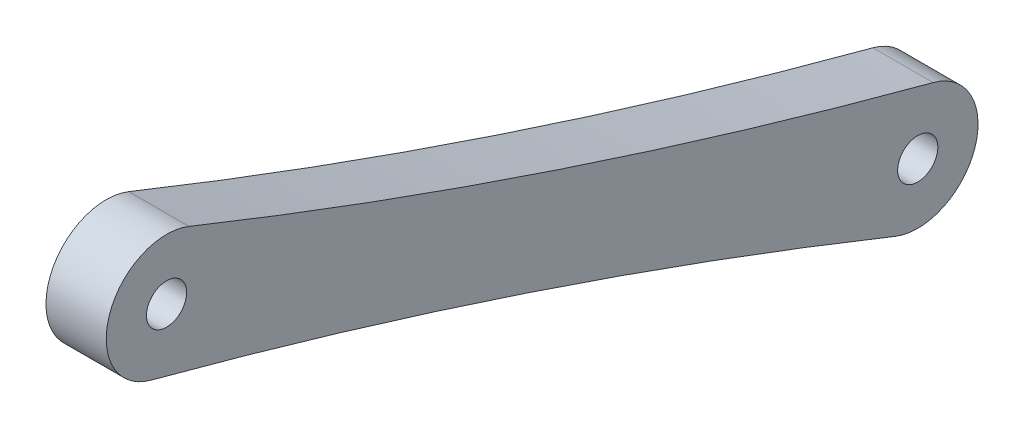
SolidWorks part; units mm, degrees
ref_plane "Front Plane" through (0, 0, 0) normal (1, 0, 0) x (0, 1, 0)
ref_plane "Top Plane" through (0, 0, 0) normal (0, 0, 1) x (0, 1, 0)
ref_plane "Right Plane" through (0, 0, 0) normal (0, 1, 0) x (-1, 0, 0)
sketch "Sketch1" plane through (0, 0, 0) normal (1, 0, 0) x (0, 1, 0)
  line L0 (34.9544, 81.6423) -> (174.7722, 81.6423) construction
  line L1 (43.2231, 11.8043) -> (59.6898, 57.9545)
  line L2 (59.6898, 57.9545) -> (27.5087, 75.5973)
  line L3 (27.5087, 75.5973) -> (43.2231, 11.8043)
  line L4 (59.6898, 57.9545) -> (114.4197, 86.8725)
  line L5 (114.4197, 86.8725) -> (92.4757, 131.7998)
  line L6 (92.4757, 131.7998) -> (75.2816, 94.0293)
  line L7 (75.2816, 94.0293) -> (59.6898, 57.9545)
  line L8 (27.5087, 75.5973) -> (39.9439, 112.9835)
  line L9 (39.9439, 112.9835) -> (92.4757, 131.7998)
  line L10 (39.9439, 112.9835) -> (75.2816, 94.0293)
  line L11 (114.4197, 86.8725) -> (113.2816, 101.8293)
  dimension "D1" = 49
  dimension "D2" = 65.7
  dimension "D3" = 36.7
  dimension "D4" = 61.9
  dimension "D5" = 50
  dimension "D6" = 41.5
  dimension "D7" = 39.3
  dimension "D8" = 55.8
  dimension "D9" = 39.4
  dimension "D10" = 40.1
  dimension "D11" = 15
  dimension "D12" = 7.8
  dimension "D13" = 38
sketch "Sketch2" plane through (0, 0, 0) normal (1, 0, 0) x (0, 1, 0)
  arc A0 (19.5331, 81.6297) -> (37.5086, 75.6508) centre (27.5087, 75.5973) ccw
  arc A1 (47.9195, 106.9511) -> (29.9441, 112.93) centre (39.9439, 112.9835) ccw
  arc A2 (47.9195, 106.9511) -> (37.5086, 75.6508) centre (88.9386, 75.926) ccw
  arc A3 (19.5331, 81.6297) -> (29.9441, 112.93) centre (-21.4859, 112.6548) ccw
  circle A4 centre (39.9439, 112.9835) radius 1
  circle A5 centre (27.5087, 75.5973) radius 1
  dimension "D1" = 20
  dimension "D2" = 2
  dimension "D3" = 2
extrude "Boss-Extrude2" add sketch "Sketch2" along normal blind 3
scale "Scale1" scale about centroid uniform scaling yes scale factor 2
sketch "Sketch3" plane through (4.5, 0, 0) normal (1, 0, 0) x (0, 1, 0)
  arc A0 (51.7282, 129.4378) -> (40.3635, 133.2203) centre (46.1615, 131.6766) ccw
  arc A1 (15.7236, 59.1408) -> (27.0897, 55.3627) centre (21.2911, 56.9042) ccw
  arc A2 (51.7282, 129.4378) -> (27.0897, 55.3627) centre (643.1124, -108.4004) ccw
  arc A3 (15.7236, 59.1408) -> (40.3635, 133.2203) centre (-579.5632, 298.2796) ccw
  arc A12 (-2.6357, 75.0014) -> (16.1619, 131.5161) centre (-76.6982, 131.0192) ccw
  arc A13 (-2.6357, 75.0014) -> (51.2907, 57.0647) centre (21.2911, 56.9042) ccw
  arc A14 (70.0883, 113.5794) -> (51.2907, 57.0647) centre (144.1508, 57.5616) ccw
  arc A15 (70.0883, 113.5794) -> (16.1619, 131.5161) centre (46.1615, 131.6766) ccw
  arc A16 (-2.6357, 75.0014) -> (16.1619, 131.5161) centre (-76.6982, 131.0192) ccw
  arc A17 (-2.6357, 75.0014) -> (51.2907, 57.0647) centre (21.2911, 56.9042) ccw
  arc A18 (70.0883, 113.5794) -> (51.2907, 57.0647) centre (144.1508, 57.5616) ccw
  arc A19 (70.0883, 113.5794) -> (16.1619, 131.5161) centre (46.1615, 131.6766) ccw
  point P1 (643.1124, -108.4004)
  point P13 (-579.5632, 298.2796)
  arc M10 (26.1618, 131.5696) -> (5.3399, 68.969) centre (-76.6982, 131.0192) cw
  arc M11 (5.3399, 68.969) -> (41.2908, 57.0112) centre (21.2911, 56.9042) ccw
  arc M12 (41.2908, 57.0112) -> (62.1127, 119.6118) centre (144.1508, 57.5616) cw
  arc M13 (62.1127, 119.6118) -> (26.1618, 131.5696) centre (46.1615, 131.6766) ccw
  dimension "D1" = 12
  dimension "D2" = 12
  dimension "D3" = 10
extrude "Cut-Extrude1" cut sketch "Sketch3" against normal through all both and the other way through all contours A18 A19 A16 A17 M10 M13 M12 M11 | A1 A3 A0 A2 M13 M10 M11 M12
